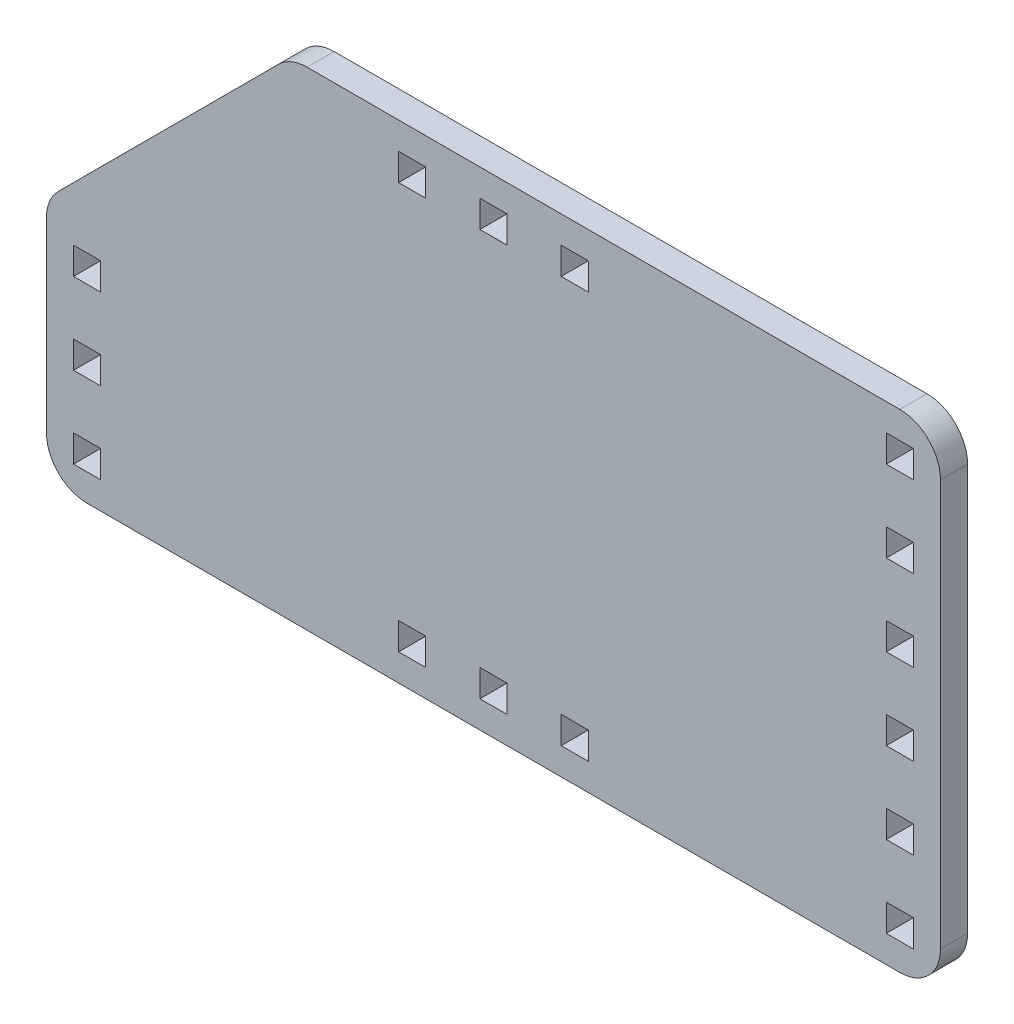
SolidWorks part; units mm, degrees
ref_plane "Alzado" through (0, 0, 0) normal (0, 0, 1) x (1, 0, 0)
ref_plane "Planta" through (0, 0, 0) normal (0, 1, 0) x (1, 0, 0)
ref_plane "Vista lateral" through (0, 0, 0) normal (1, 0, 0) x (0, 0, -1)
sketch "Model" plane through (0, 0, 0) normal (0, 0, 1) x (1, 0, 0)
  line L0 (12.4128, 254.7571) -> (12.4128, 251.7571)
  line L1 (15.4128, 254.7571) -> (12.4128, 254.7571)
  line L2 (15.4128, 251.7571) -> (15.4128, 254.7571)
  line L3 (12.4128, 251.7571) -> (15.4128, 251.7571)
  line L4 (102.4128, 245.7571) -> (102.4128, 242.7571)
  line L5 (105.4128, 245.7571) -> (102.4128, 245.7571)
  line L6 (105.4128, 242.7571) -> (105.4128, 245.7571)
  line L7 (102.4128, 242.7571) -> (105.4128, 242.7571)
  line L8 (102.4128, 290.7571) -> (102.4128, 287.7571)
  line L9 (105.4128, 290.7571) -> (102.4128, 290.7571)
  line L10 (105.4128, 287.7571) -> (105.4128, 290.7571)
  line L11 (102.4128, 287.7571) -> (105.4128, 287.7571)
  line L12 (57.4128, 290.7571) -> (57.4128, 287.7571)
  line L13 (60.4128, 290.7571) -> (57.4128, 290.7571)
  line L14 (60.4128, 287.7571) -> (60.4128, 290.7571)
  line L15 (57.4128, 287.7571) -> (60.4128, 287.7571)
  line L16 (102.4128, 254.7571) -> (102.4128, 251.7571)
  line L17 (105.4128, 254.7571) -> (102.4128, 254.7571)
  line L18 (105.4128, 251.7571) -> (105.4128, 254.7571)
  line L19 (102.4128, 251.7571) -> (105.4128, 251.7571)
  line L20 (102.4128, 281.7571) -> (102.4128, 278.7571)
  line L21 (105.4128, 281.7571) -> (102.4128, 281.7571)
  line L22 (105.4128, 278.7571) -> (105.4128, 281.7571)
  line L23 (102.4128, 278.7571) -> (105.4128, 278.7571)
  line L24 (66.4128, 290.7571) -> (66.4128, 287.7571)
  line L25 (69.4128, 290.7571) -> (66.4128, 290.7571)
  line L26 (69.4128, 287.7571) -> (69.4128, 290.7571)
  line L27 (66.4128, 287.7571) -> (69.4128, 287.7571)
  line L28 (48.4128, 290.7571) -> (48.4128, 287.7571)
  line L29 (51.4128, 290.7571) -> (48.4128, 290.7571)
  line L30 (51.4128, 287.7571) -> (51.4128, 290.7571)
  line L31 (48.4128, 287.7571) -> (51.4128, 287.7571)
  line L32 (102.4128, 272.7571) -> (102.4128, 269.7571)
  line L33 (105.4128, 272.7571) -> (102.4128, 272.7571)
  line L34 (105.4128, 269.7571) -> (105.4128, 272.7571)
  line L35 (102.4128, 269.7571) -> (105.4128, 269.7571)
  line L36 (102.4128, 263.7571) -> (102.4128, 260.7571)
  line L37 (105.4128, 263.7571) -> (102.4128, 263.7571)
  line L38 (105.4128, 260.7571) -> (105.4128, 263.7571)
  line L39 (102.4128, 260.7571) -> (105.4128, 260.7571)
  line L40 (57.4128, 245.7571) -> (57.4128, 242.7571)
  line L41 (60.4128, 245.7571) -> (57.4128, 245.7571)
  line L42 (60.4128, 242.7571) -> (60.4128, 245.7571)
  line L43 (57.4128, 242.7571) -> (60.4128, 242.7571)
  line L44 (66.4128, 245.7571) -> (66.4128, 242.7571)
  line L45 (69.4128, 245.7571) -> (66.4128, 245.7571)
  line L46 (69.4128, 242.7571) -> (69.4128, 245.7571)
  line L47 (66.4128, 242.7571) -> (69.4128, 242.7571)
  line L48 (48.4128, 245.7571) -> (48.4128, 242.7571)
  line L49 (51.4128, 245.7571) -> (48.4128, 245.7571)
  line L50 (51.4128, 242.7571) -> (51.4128, 245.7571)
  line L51 (48.4128, 242.7571) -> (51.4128, 242.7571)
  line L52 (12.4128, 245.7571) -> (12.4128, 242.7571)
  line L53 (15.4128, 245.7571) -> (12.4128, 245.7571)
  line L54 (15.4128, 242.7571) -> (15.4128, 245.7571)
  line L55 (12.4128, 242.7571) -> (15.4128, 242.7571)
  line L56 (12.4128, 263.7571) -> (12.4128, 260.7571)
  line L57 (15.4128, 263.7571) -> (12.4128, 263.7571)
  line L58 (15.4128, 260.7571) -> (15.4128, 263.7571)
  line L59 (12.4128, 260.7571) -> (15.4128, 260.7571)
  line L60 (13.9128, 239.7571) -> (103.9128, 239.7571)
  line L61 (108.4128, 244.2571) -> (108.4128, 289.2571)
  line L62 (103.9128, 293.7571) -> (38.2767, 293.7571)
  line L63 (9.4128, 264.8932) -> (9.4128, 244.2571)
  line L64 (10.7308, 268.0752) -> (35.0948, 292.4391)
  arc A0 (108.4128, 289.2571) -> (103.9128, 293.7571) centre (103.9128, 289.2571) ccw
  arc A1 (103.9128, 239.7571) -> (108.4128, 244.2571) centre (103.9128, 244.2571) ccw
  arc A2 (9.4128, 244.2571) -> (13.9128, 239.7571) centre (13.9128, 244.2571) ccw
  arc A3 (10.7308, 268.0752) -> (9.4128, 264.8932) centre (13.9128, 264.8932) ccw
  arc A4 (38.2767, 293.7571) -> (35.0948, 292.4391) centre (38.2767, 289.2571) ccw
extrude "Saliente-Extruir1" add sketch "Model" along normal blind 3
